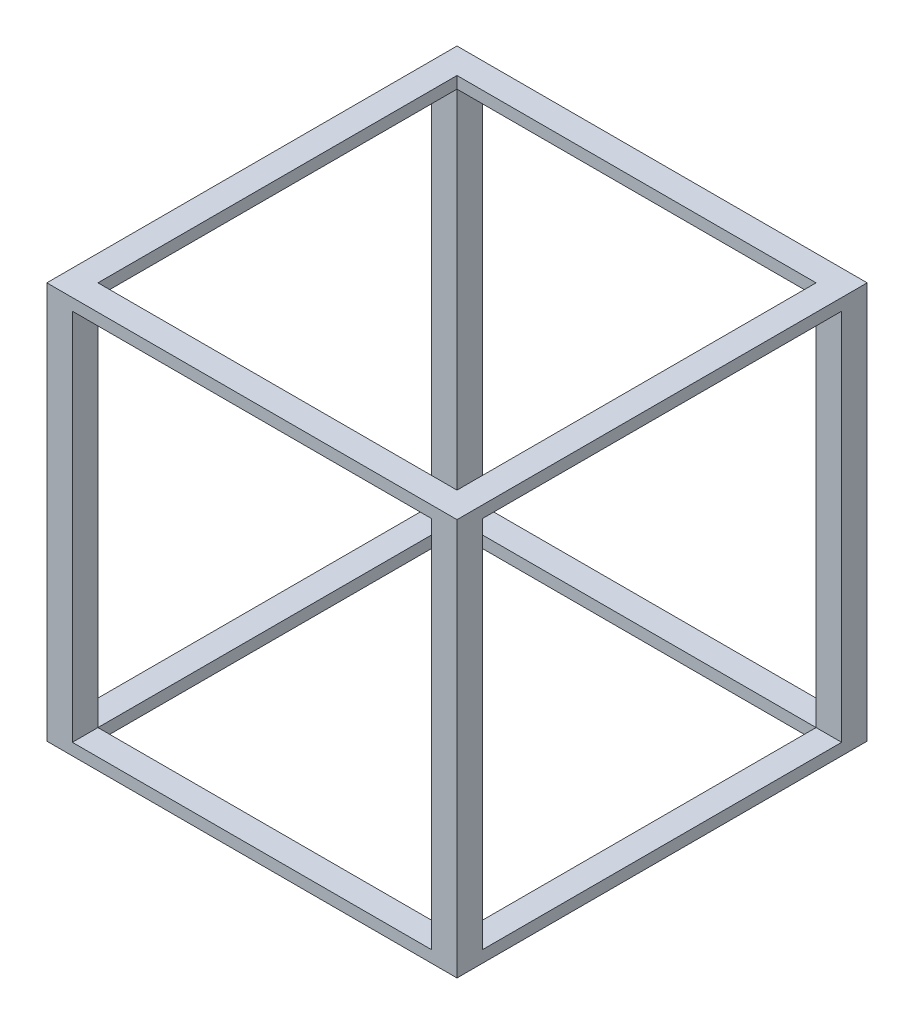
SolidWorks part; units mm, degrees
ref_plane "Front Plane" through (0, 0, 0) normal (0, 0, 1) x (1, 0, 0)
ref_plane "Top Plane" through (0, 0, 0) normal (0, 1, 0) x (1, 0, 0)
ref_plane "Right Plane" through (0, 0, 0) normal (1, 0, 0) x (0, 0, -1)
sketch "Sketch1" plane through (0, 0, 0) normal (0, 1, 0) x (1, 0, 0)
  line L1 (-52.1805, -52.1805) -> (52.1805, -52.1805)
  line L2 (-52.1805, -52.1805) -> (-52.1805, 52.1805)
  line L3 (-52.1805, 52.1805) -> (52.1805, 52.1805)
  line L4 (52.1805, -52.1805) -> (52.1805, 52.1805)
  line L5 (-52.1805, -52.1805) -> (52.1805, 52.1805) construction
  line L6 (-52.1805, 52.1805) -> (52.1805, -52.1805) construction
  line L7 (45.6805, -45.6805) -> (-45.6805, -45.6805)
  line L8 (45.6805, -45.6805) -> (45.6805, 45.6805)
  line L9 (45.6805, 45.6805) -> (-45.6805, 45.6805)
  line L10 (-45.6805, -45.6805) -> (-45.6805, 45.6805)
  line L11 (45.6805, -45.6805) -> (-45.6805, 45.6805) construction
  line L12 (45.6805, 45.6805) -> (-45.6805, -45.6805) construction
  point P0 (0, 0)
  point P6 (0, 0)
  dimension "D1" = 104.361
  dimension "D2" = 6.5
extrude "Boss-Extrude1" add sketch "Sketch1" along normal blind 3
sketch "Sketch2" plane through (0, 3, 0) normal (0, 1, 0) x (1, 0, 0)
  line L1 (-52.1805, 52.1805) -> (-45.6805, 52.1805)
  line L2 (-52.1805, 52.1805) -> (-52.1805, 45.6805)
  line L3 (-52.1805, 45.6805) -> (-45.6805, 45.6805)
  line L4 (-45.6805, 52.1805) -> (-45.6805, 45.6805)
  line L5 (52.1805, 52.1805) -> (45.6805, 52.1805)
  line L6 (52.1805, 52.1805) -> (52.1805, 45.6805)
  line L7 (52.1805, 45.6805) -> (45.6805, 45.6805)
  line L8 (45.6805, 52.1805) -> (45.6805, 45.6805)
  line L9 (-45.6805, -45.6805) -> (-52.1805, -45.6805)
  line L10 (-45.6805, -45.6805) -> (-45.6805, -52.1805)
  line L11 (-45.6805, -52.1805) -> (-52.1805, -52.1805)
  line L12 (-52.1805, -45.6805) -> (-52.1805, -52.1805)
  line L13 (45.6805, -45.6805) -> (52.1805, -45.6805)
  line L14 (45.6805, -45.6805) -> (45.6805, -52.1805)
  line L15 (45.6805, -52.1805) -> (52.1805, -52.1805)
  line L16 (52.1805, -45.6805) -> (52.1805, -52.1805)
extrude "Boss-Extrude2" add sketch "Sketch2" along normal blind 95
sketch "Sketch3" plane through (0, 98, 0) normal (0, 1, 0) x (1, 0, 0)
  line L1 (-52.1805, 52.1805) -> (52.1805, 52.1805)
  line L2 (-52.1805, 52.1805) -> (-52.1805, -52.1805)
  line L3 (-52.1805, -52.1805) -> (52.1805, -52.1805)
  line L4 (52.1805, 52.1805) -> (52.1805, -52.1805)
  line L5 (-45.6805, 45.6805) -> (45.6805, 45.6805)
  line L6 (-45.6805, 45.6805) -> (-45.6805, -45.6805)
  line L7 (-45.6805, -45.6805) -> (45.6805, -45.6805)
  line L8 (45.6805, 45.6805) -> (45.6805, -45.6805)
extrude "Boss-Extrude3" add sketch "Sketch3" along normal blind 3
